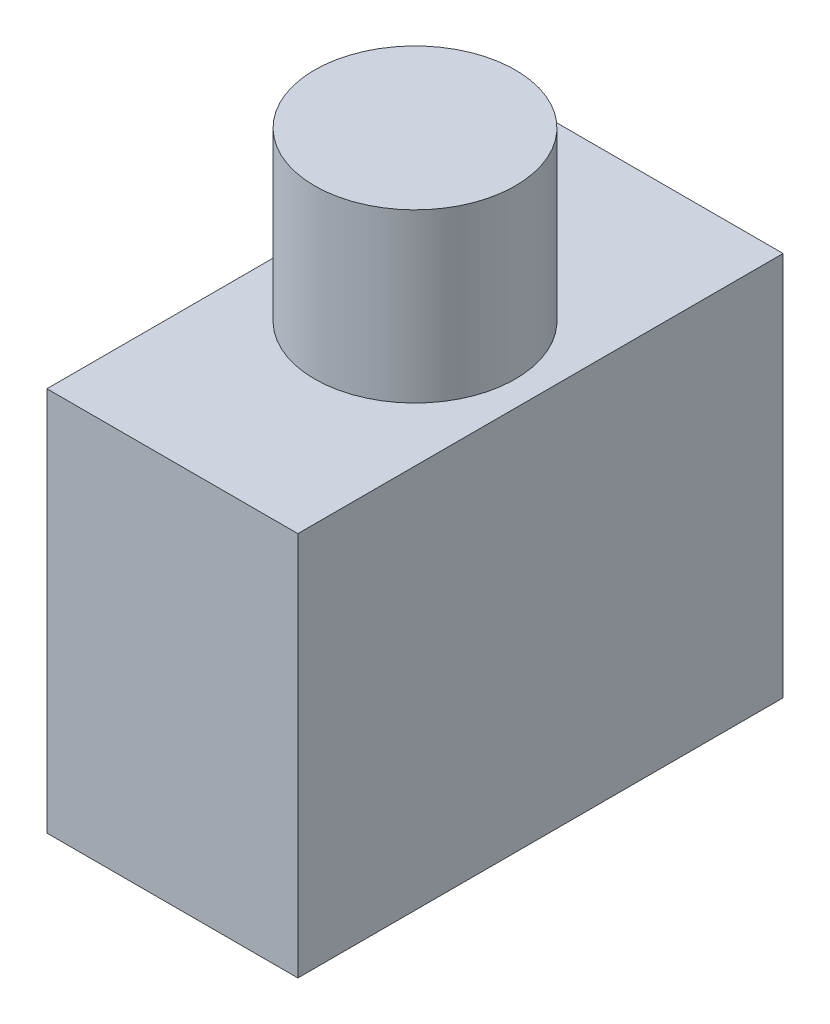
SolidWorks part; units mm, degrees
ref_plane "前视基准面" through (0, 0, 0) normal (0, 0, 1) x (1, 0, 0)
ref_plane "上视基准面" through (0, 0, 0) normal (0, 1, 0) x (1, 0, 0)
ref_plane "右视基准面" through (0, 0, 0) normal (1, 0, 0) x (0, 0, -1)
sketch "草图1" plane through (0, 0, 0) normal (0, 1, 0) x (1, 0, 0)
  line L1 (-7.5, 14.5) -> (7.5, 14.5)
  line L2 (-7.5, 14.5) -> (-7.5, -14.5)
  line L3 (-7.5, -14.5) -> (7.5, -14.5)
  line L4 (7.5, 14.5) -> (7.5, -14.5)
  line L5 (-7.5, 14.5) -> (7.5, -14.5) construction
  line L6 (-7.5, -14.5) -> (7.5, 14.5) construction
  point P0 (0, 0)
  dimension "D1" = 15
  dimension "D2" = 29
extrude "凸台-拉伸1" add sketch "草图1" along normal blind 23
sketch "草图2" plane through (0, 23, 0) normal (0, 1, 0) x (1, 0, 0)
  circle A0 centre (0, 0) radius 6
  dimension "D1" = 12
extrude "凸台-拉伸2" add sketch "草图2" along normal blind 10
